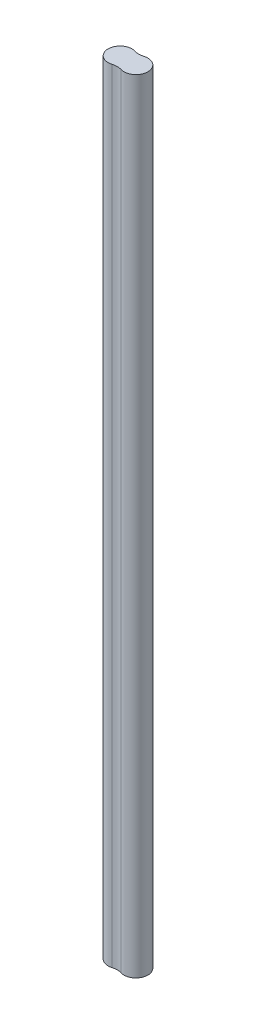
SolidWorks part; units mm, degrees
ref_plane "Front Plane" through (0, 0, 0) normal (0, 0, 1) x (1, 0, 0)
ref_plane "Top Plane" through (0, 0, 0) normal (0, 1, 0) x (1, 0, 0)
ref_plane "Right Plane" through (0, 0, 0) normal (1, 0, 0) x (0, 0, -1)
sketch "Sketch1" plane through (0, 0, 0) normal (0, 1, 0) x (1, 0, 0)
  line L0 (0, 0) -> (2.032, 0) construction
  line L1 (0, 1.524) -> (2.032, 1.524)
  line L2 (0, -1.524) -> (2.032, -1.524)
  arc A0 (0, 1.524) -> (0, -1.524) centre (0, 0) ccw
  arc A1 (2.032, -1.524) -> (2.032, 1.524) centre (2.032, 0) ccw
  circle A2 centre (0, 0) radius 1.524
  circle A3 centre (2.032, 0) radius 1.524
  point P3 (1.016, 0)
  dimension "D2" = 5.08
  dimension "D1" = 3.048
extrude "Boss-Extrude1" add sketch "Sketch1" along normal blind 100
fillet "Fillet1" radius 2 2 edges at (1.016, 50, 1.1359) (1.016, 50, -1.1359)
